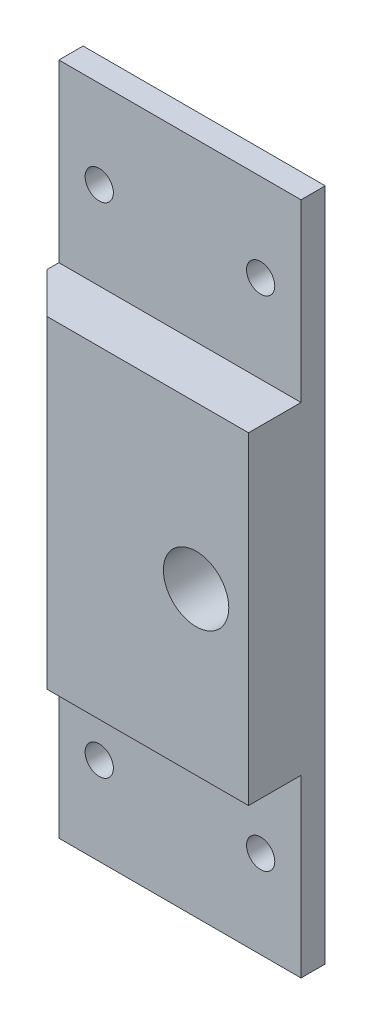
SolidWorks part; units mm, degrees
ref_plane "Front Plane" through (0, 0, 0) normal (0, 0, 1) x (1, 0, 0)
ref_plane "Top Plane" through (0, 0, 0) normal (0, 1, 0) x (1, 0, 0)
ref_plane "Right Plane" through (0, 0, 0) normal (1, 0, 0) x (0, 0, -1)
sketch "Sketch1" plane through (0, 0, 0) normal (0, 0, 1) x (1, 0, 0)
  line L1 (0, 0) -> (30, 0)
  line L2 (0, 0) -> (0, 83.5)
  line L3 (0, 83.5) -> (30, 83.5)
  line L4 (30, 0) -> (30, 83.5)
  dimension "D1" = 83.5
  dimension "D2" = 30
extrude "Boss-Extrude1" add sketch "Sketch1" along normal blind 3
sketch "Sketch2" plane through (0, 0, 3) normal (0, 0, 1) x (1, 0, 0)
  line L0 (0, 83.5) -> (0, 0) construction
  line L1 (0, 61.75) -> (30, 61.75)
  line L2 (0, 61.75) -> (0, 21.75)
  line L3 (0, 21.75) -> (30, 21.75)
  line L4 (30, 61.75) -> (30, 21.75)
  line L5 (30, 0) -> (30, 83.5) construction
  line L6 (30, 0) -> (30, 83.5) construction
  point P8 (0, 41.75)
  point P11 (30, 41.75)
  dimension "D1" = 40
  dimension "D2" = 0
extrude "Boss-Extrude2" add sketch "Sketch2" along normal blind 6.5
sketch "Sketch3" plane through (0, 0, 3) normal (0, 0, 1) x (1, 0, 0)
  line L0 (0, 10.875) -> (5, 10.875) construction
  line L1 (0, 21.75) -> (0, 0) construction
  line L2 (25, 10.875) -> (30, 10.875) construction
  line L3 (30, 0) -> (30, 21.75) construction
  circle A0 centre (5, 10.875) radius 1.75
  circle A1 centre (25, 10.875) radius 1.75
  dimension "D1" = 3.5
  dimension "D2" = 3.5
  dimension "D3" = 5
extrude "Cut-Extrude1" cut sketch "Sketch3" against normal blind 7
ref_plane "Plane1" through (0, 41.75, 0) normal (0, -1, 0) x (-1, 0, 0)
mirror "Mirror1" about plane through (0, 41.75, 0) normal (0, -1, 0) of "Cut-Extrude1"
sketch "Sketch4" plane through (0, 0, 9.5) normal (0, 0, 1) x (1, 0, 0)
  line L0 (0, 41.75) -> (30, 41.75) construction
  line L1 (0, 61.75) -> (0, 21.75) construction
  line L2 (30, 21.75) -> (30, 61.75) construction
  circle A0 centre (23.5, 41.75) radius 4.05
  dimension "D1" = 8.1
  dimension "D2" = 6.5
extrude "Cut-Extrude2" cut sketch "Sketch4" against normal blind 24
sketch "Sketch5" plane through (0, 0, 0) normal (0, 0, -1) x (-1, 0, 0)
  circle A0 centre (-5, 72.625) radius 3
  circle A1 centre (-25, 72.625) radius 3
  circle A2 centre (-5, 10.875) radius 3
  circle A3 centre (-25, 10.875) radius 3
  dimension "D1" = 6
chamfer "Chamfer1" distance 5 angle 45 1 edges at (0, 41.75, 9.5)
